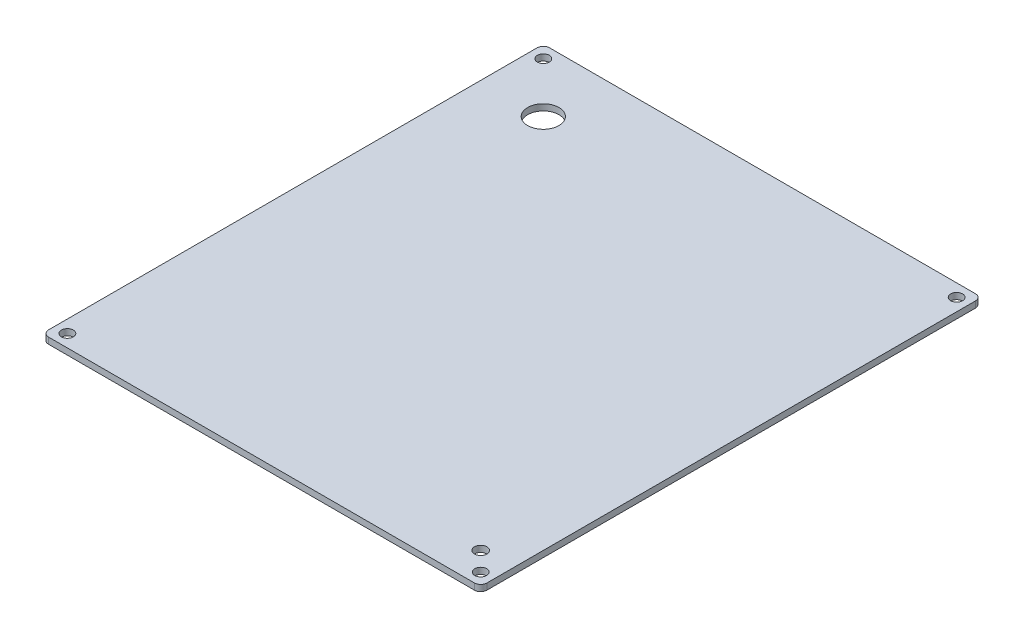
SolidWorks part; units mm, degrees
ref_plane "Front Plane" through (0, 0, 0) normal (0, 0, 1) x (1, 0, 0)
ref_plane "Top Plane" through (0, 0, 0) normal (0, 1, 0) x (1, 0, 0)
ref_plane "Right Plane" through (0, 0, 0) normal (1, 0, 0) x (0, 0, -1)
sketch "Sketch1" plane through (0, 0, 0) normal (0, 1, 0) x (1, 0, 0)
  line L1 (0, 0) -> (140, 0)
  line L2 (0, 0) -> (0, 160)
  line L3 (0, 160) -> (140, 160)
  line L4 (140, 0) -> (140, 160)
  dimension "D1" = 140
  dimension "D2" = 160
extrude "Boss-Extrude1" add sketch "Sketch1" along normal blind 2
sketch "Sketch2" plane through (0, 2, 0) normal (0, 1, 0) x (1, 0, 0)
  line L0 (4, 160) -> (4, 156) construction
  line L1 (140, 160) -> (0, 160) construction
  line L2 (4, 156) -> (0, 156) construction
  line L3 (0, 160) -> (0, 0) construction
  line L4 (70, 160) -> (70, 0) construction
  line L5 (0, 0) -> (140, 0) construction
  line L6 (0, 80) -> (140, 80) construction
  line L7 (140, 0) -> (140, 160) construction
  line L8 (136, 156) -> (140, 156) construction
  line L9 (136, 160) -> (136, 156) construction
  line L10 (136, 0) -> (136, 4) construction
  line L11 (136, 4) -> (140, 4) construction
  line L12 (4, 4) -> (0, 4) construction
  line L13 (4, 0) -> (4, 4) construction
  line L14 (130, 10) -> (130, 0) construction
  line L15 (130, 10) -> (140, 10) construction
  line L16 (0, 140) -> (20, 140) construction
  line L17 (20, 140) -> (20, 160) construction
  circle A0 centre (4, 156) radius 1.9
  circle A1 centre (136, 156) radius 1.9
  circle A2 centre (136, 4) radius 1.9
  circle A3 centre (4, 4) radius 1.9
  circle A4 centre (130, 10) radius 2
  circle A5 centre (20, 140) radius 5
  dimension "D2" = 3.8
  dimension "D5" = 4
  dimension "D8" = 10
  dimension "D1" = 4
  dimension "D3" = 10
  dimension "D4" = 10
  dimension "D6" = 20
  dimension "D7" = 20
extrude "Cut-Extrude1" cut sketch "Sketch2" against normal blind 10
fillet "Fillet1" radius 2 4 edges at (0, 1, 0) (140, 1, 0) (140, 1, -160) (0, 1, -160)
